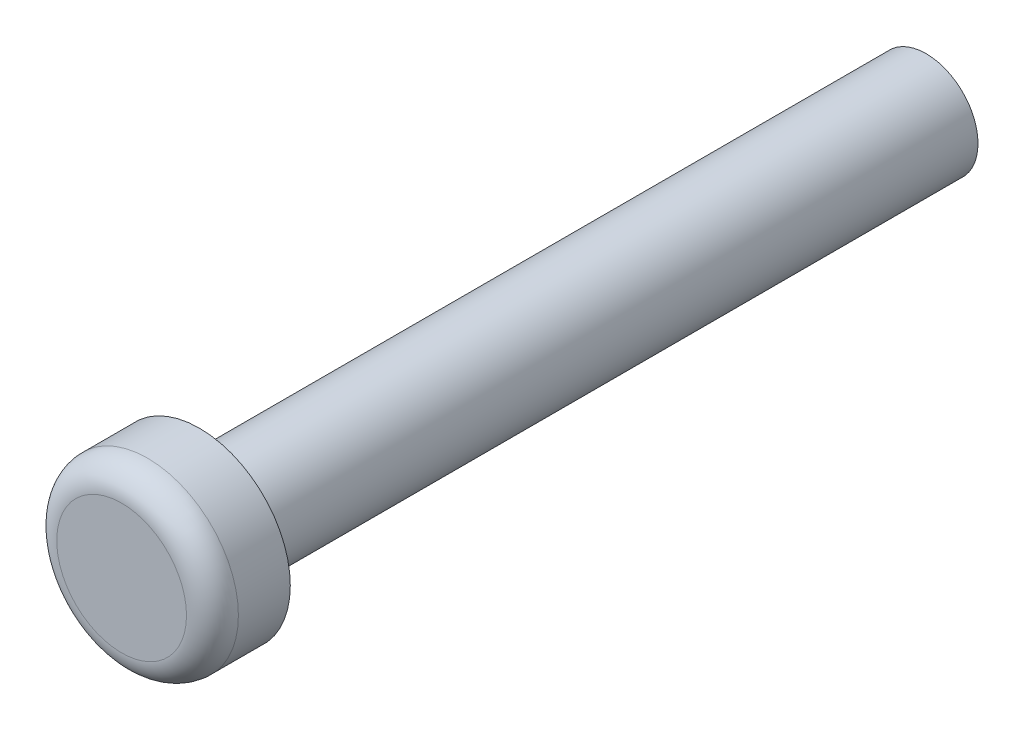
SolidWorks part; units mm, degrees
material "AISI Type 316L stainless steel"
ref_plane "Front Plane" through (0, 0, 0) normal (0, 0, 1) x (1, 0, 0)
ref_plane "Top Plane" through (0, 0, 0) normal (0, 1, 0) x (1, 0, 0)
ref_plane "Right Plane" through (0, 0, 0) normal (1, 0, 0) x (0, 0, -1)
sketch "Sketch1" plane through (0, 0, 0) normal (0, 0, 1) x (1, 0, 0)
  circle A1 centre (0, 0) radius 4.445
  dimension "D2" = 8.89
extrude "Boss-Extrude1" add sketch "Sketch1" along normal blind 3.81
fillet "Fillet2" radius 1.27 1 edges at (4.445, 0, 3.81)
sketch "Sketch2" plane through (0, 0, 0) normal (0, 0, -1) x (-1, 0, 0)
  circle A0 centre (0, 0) radius 2.54
  dimension "D1" = 5.08
extrude "Boss-Extrude2" add sketch "Sketch2" along normal blind 35.56
move or copy body "Body-Move/Copy1" [suppressed] bodies to move or copy 102
